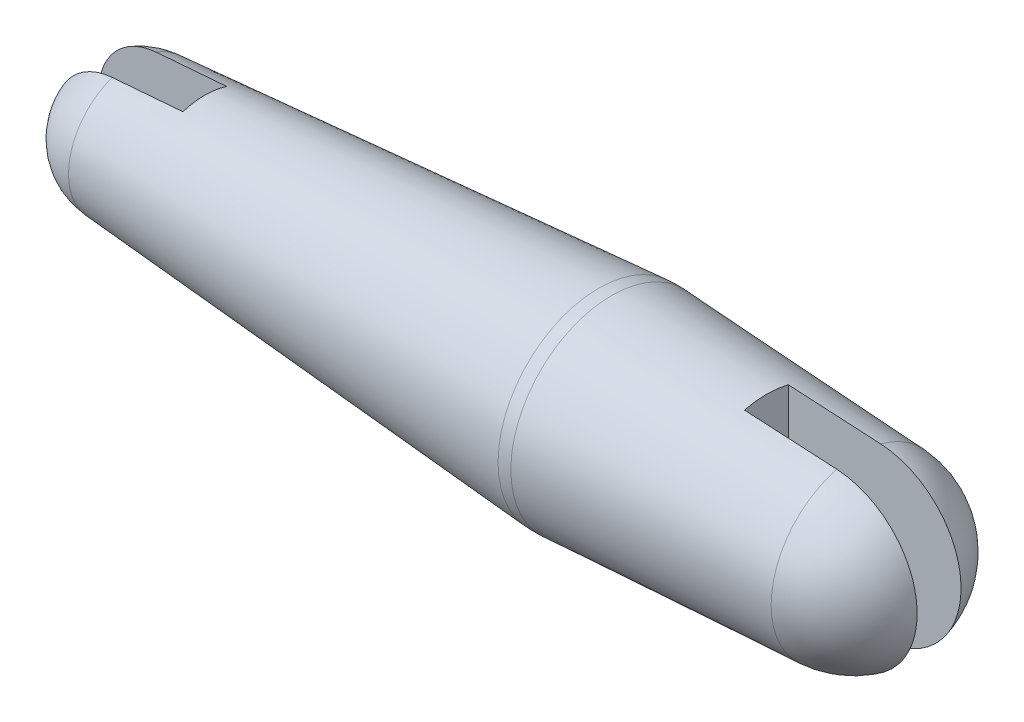
SolidWorks part; units mm, degrees
ref_plane "Front Plane" through (0, 0, 0) normal (0, 0, 1) x (1, 0, 0)
ref_plane "Top Plane" through (0, 0, 0) normal (0, 1, 0) x (1, 0, 0)
ref_plane "Right Plane" through (0, 0, 0) normal (1, 0, 0) x (0, 0, -1)
sketch "Sketch1" plane through (0, 0, 0) normal (0, 0, 1) x (1, 0, 0)
  line L0 (-207.01, 0) -> (207.01, 0)
  line L1 (-209.872, 37.9924) -> (59.1116, 58.2549)
  line L2 (209.7073, 50.7283) -> (66.6019, 58.3376)
  line L3 (-207.01, 0) -> (-245.11, 0)
  line L4 (207.01, 0) -> (257.81, 0)
  arc A0 (66.6019, 58.3376) -> (59.1116, 58.2549) centre (63.5, 0) ccw
  arc A1 (257.81, 0) -> (209.7073, 50.7283) centre (207.01, 0) ccw
  arc A2 (-209.872, 37.9924) -> (-245.11, 0) centre (-207.01, 0) ccw
  dimension "D2" = 116.84
  dimension "D3" = 101.6
  dimension "D4" = 76.2
  dimension "D1" = 414.02
  dimension "D5" = 63.5
  dimension "D6" = 502.92
  dimension "D7" = 207.01
revolve "Revolve1" add sketch "Sketch1" angle 360 about L0
sketch "Sketch2" plane through (0, 0, 0) normal (0, 1, 0) x (1, 0, 0)
  line L0 (257.81, -1044.0903) -> (257.81, 48955.9097) construction
  line L1 (-1000, 0) -> (49000, 0) construction
  line L2 (-245.11, -981.86) -> (-245.11, 49018.14) construction
  line L3 (156.21, 12.7) -> (257.81, 12.7)
  line L4 (156.21, 12.7) -> (156.21, -12.7)
  line L5 (156.21, -12.7) -> (257.81, -12.7)
  line L6 (257.81, 12.7) -> (257.81, -12.7)
  line L7 (156.21, 12.7) -> (257.81, -12.7) construction
  line L8 (156.21, -12.7) -> (257.81, 12.7) construction
  line L10 (-245.11, 12.7) -> (-168.91, 12.7)
  line L11 (-245.11, 12.7) -> (-245.11, -12.7)
  line L12 (-245.11, -12.7) -> (-168.91, -12.7)
  line L13 (-168.91, 12.7) -> (-168.91, -12.7)
  line L14 (-245.11, 12.7) -> (-168.91, -12.7) construction
  line L15 (-245.11, -12.7) -> (-168.91, 12.7) construction
  arc A0 (209.7073, -50.7283) -> (209.7073, 50.7283) centre (207.01, 0) ccw construction
  arc A1 (-209.872, 37.9924) -> (-209.872, -37.9924) centre (-207.01, 0) ccw construction
  point P6 (207.01, 0)
  point P18 (-207.01, 0)
  dimension "D1" = 25.4
  dimension "D2" = 101.6
  dimension "D3" = 25.4
  dimension "D4" = 76.2
extrude "Cut-Extrude1" cut sketch "Sketch2" against normal through all and the other way through all
sketch3d "3DSketch1"
  line L0 (-245.11, 0, 0) -> (257.81, 0, 0)
  line L1 (-207.01, 0, -254) -> (-207.01, 0, 254)
  line L2 (207.01, 0, -254) -> (207.01, 0, 254)
  point P3 (-207.01, 0, 0)
  point P4 (207.01, 0, 0)
  point P5 (0, 0, 0)
  point P6 (0, 0, 0)
  dimension "D1" = 207.01
  dimension "D2" = 207.01
  dimension "D3" = 508
